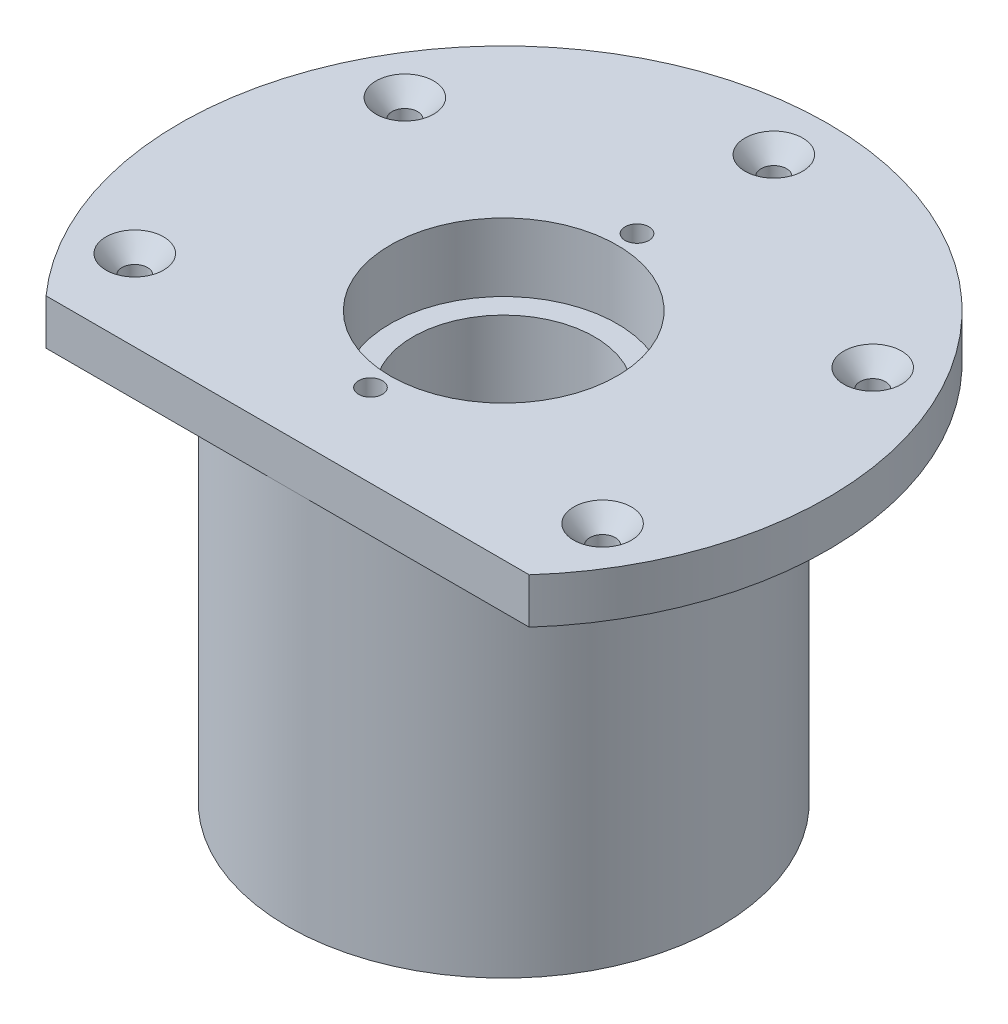
SolidWorks part; units mm, degrees
ref_plane "Front Plane" through (0, 0, 0) normal (0, 0, 1) x (1, 0, 0)
ref_plane "Top Plane" through (0, 0, 0) normal (0, 1, 0) x (1, 0, 0)
ref_plane "Right Plane" through (0, 0, 0) normal (1, 0, 0) x (0, 0, -1)
sketch "Sketch1" plane through (0, 0, 0) normal (0, 1, 0) x (1, 0, 0)
  circle A0 centre (0, 0) radius 38.1
  circle A1 centre (0, 0) radius 20
  dimension "D1" = 76.2
  dimension "D2" = 40
extrude "Boss-Extrude1" add sketch "Sketch1" along normal blind 75
sketch "Sketch2" plane through (0, 75, 0) normal (0, 1, 0) x (1, 0, 0)
  line L0 (-42.5971, -38.1) -> (42.5971, -38.1)
  circle A0 centre (0, 0) radius 57.15
  circle A1 centre (0, 0) radius 20 construction
  circle A2 centre (0, 0) radius 20
  circle A3 centre (0, 0) radius 38.1 construction
  circle M1 centre (0, 0) radius 38.1
  circle M2 centre (0, 0) radius 20
  dimension "D1" = 114.3
extrude "Boss-Extrude2" add sketch "Sketch2" against normal blind 8 contours L0 A0 M1 | M1 M2
hole_wizard "CSK for #8 Flat Head Machine Screw2" positions "Sketch3" profile "Sketch4" countersink size "#8" standard "ANSI Inch" end condition through all
sketch "Sketch3" plane through (0, 75, 0) normal (0, 1, 0) x (1, 0, 0)
  line L0 (-41.2445, -23.8125) -> (0, 0) construction
  line L2 (-41.25, 0) -> (41.25, 0) construction
  line L3 (-32.9956, -19.05) -> (-49.4934, -28.575) construction
  line L4 (0, 0) -> (-41.2445, -23.8125) construction
  arc A0 (42.5971, -38.1) -> (-42.5971, -38.1) centre (0, 0) ccw construction
  circle A1 centre (0, 0) radius 38.1 construction
  circle A2 centre (0, 0) radius 38.1 construction
  point P0 (-41.2445, -23.8125)
  point P32 (-41.2445, 23.8125)
  point P33 (0, 47.625)
  point P34 (41.2445, 23.8125)
  point P35 (41.2445, -23.8125)
  point P36 (0, -47.625) [skipped]
  dimension "D1" = 30
  dimension "D2" = 6
sketch "Sketch4" plane through (-41.2445, 75, 23.8125) normal (1, 0, 0) x (0, 0, 1)
  line L0 (0, 0) -> (0, 75)
  line L1 (0, 75) -> (2.2479, 75)
  line L2 (2.2479, 75) -> (2.2479, 3.2645)
  line L3 (2.2479, 3.2645) -> (5.0857, 0)
  line L5 (5.0857, 0) -> (0, 0)
  line L6 (-2.2479, 3.2645) -> (-5.0857, 0) construction
  line L11 (0, -6.35) -> (0, 107.95) construction
  dimension "Thru Hole Dia." = 4.4958
  dimension "Thru Hole Depth" = 75
  dimension "Near C'Sink Dia." = 10.1714
  dimension "Near C'Sink Angle" = 82
sketch "Sketch5" plane through (0, 75, 0) normal (0, 1, 0) x (1, 0, 0)
  circle A0 centre (0, 0) radius 20 construction
  circle A1 centre (0, 0) radius 20
  circle A2 centre (0, 0) radius 16
  dimension "D1" = 4
extrude "Boss-Extrude3" add sketch "Sketch5" against normal offset from surface (51 mm away) 12 from offset 12 up to face at (0, 0, 38.1) offset against normal yes
hole_wizard "Tap Drill for M5x0.8 Tap1" positions "Sketch6" profile "Sketch7" hole size "M5x0.8" standard "ANSI Metric" end condition through all
sketch "Sketch6" plane through (0, 75, 0) normal (0, 1, 0) x (1, 0, 0)
  point P0 (0, 23.5)
  point P2 (0, -23.5)
  point P6 (0, 0)
  dimension "D1" = 23.5
  dimension "D2" = 23.5
sketch "Sketch7" plane through (0, 75, -23.5) normal (1, 0, 0) x (0, 0, 1)
  line L0 (0, 0) -> (0, 75)
  line L1 (0, 75) -> (2.1, 75)
  line L2 (2.1, 75) -> (2.1, 0)
  line L5 (2.1, 0) -> (0, 0)
  line L11 (0, -6.35) -> (0, 107.95) construction
  dimension "Thru Hole Dia." = 4.2
  dimension "Thru Hole Depth" = 75
